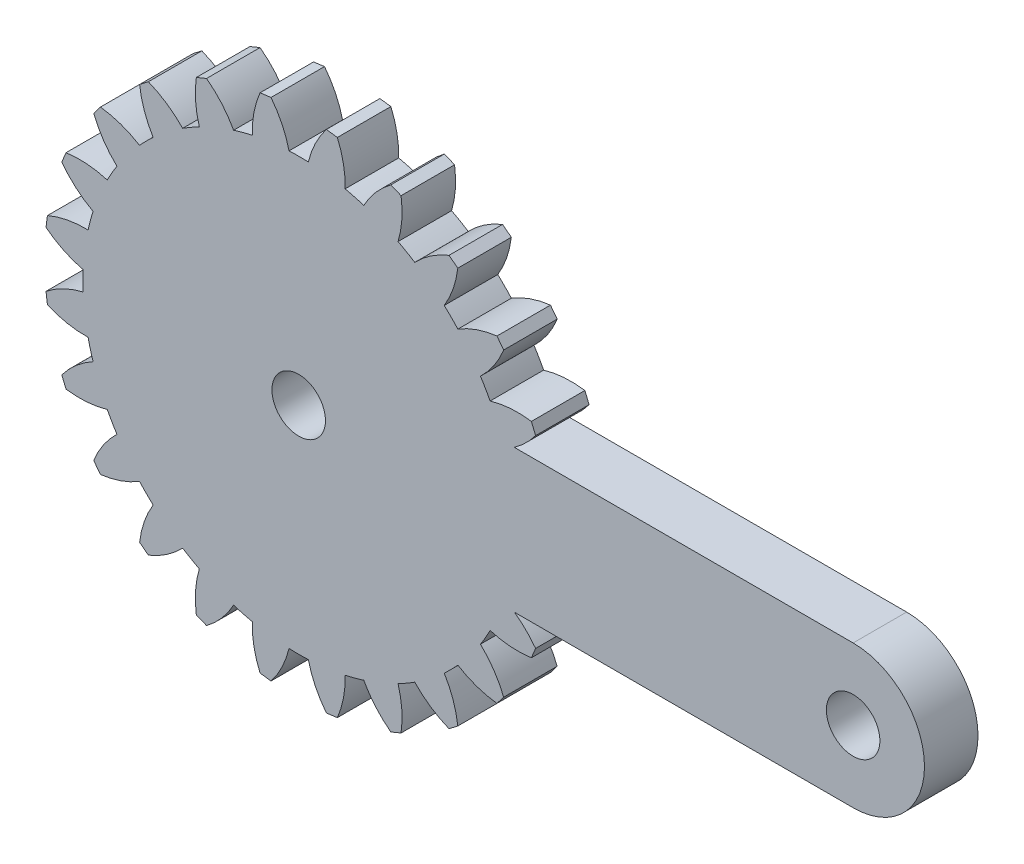
SolidWorks part; units mm, degrees
ref_plane "Front Plane" through (0, 0, 0) normal (0, 0, 1) x (1, 0, 0)
ref_plane "Top Plane" through (0, 0, 0) normal (0, 1, 0) x (1, 0, 0)
ref_plane "Right Plane" through (0, 0, 0) normal (1, 0, 0) x (0, 0, -1)
sketch "Sketch1" plane through (0, 0, 0) normal (0, 0, 1) x (1, 0, 0)
  line L0 (0, 0) -> (18.91, 0) construction
  line L1 (-0.08, 4) -> (18.91, 4)
  line L2 (-0.08, -4) -> (18.91, -4)
  line L3 (-10.0031, 14.0843) -> (-10.6178, 14.1652)
  line L4 (-12.17, 0) -> (-9.0712, 23.5377) construction
  line L5 (-12.17, -30.3062) -> (-12.17, 19.7851) construction
  line L6 (-39.8017, 0) -> (32.0176, 0) construction
  line L7 (-14.3369, 14.0843) -> (-13.7222, 14.1652)
  line L8 (-12.17, 0) -> (-15.0661, 21.9982) construction
  line L9 (-12.17, 0) -> (-9.2739, 21.9982) construction
  line L10 (-12.17, 0) -> (-3.679, 20.499) construction
  line L11 (-12.17, 0) -> (1.3372, 17.6029) construction
  line L12 (-12.17, 0) -> (5.4329, 13.5072) construction
  line L13 (-12.17, 0) -> (8.329, 8.491) construction
  line L14 (-12.17, 0) -> (9.8282, 2.8961) construction
  line L15 (-12.17, 0) -> (9.8282, -2.8961) construction
  line L16 (-12.17, 0) -> (8.329, -8.491) construction
  line L17 (-12.17, 0) -> (5.4329, -13.5072) construction
  line L18 (-12.17, 0) -> (1.3372, -17.6029) construction
  line L19 (-12.17, 0) -> (-3.679, -20.499) construction
  line L20 (-12.17, 0) -> (-9.2739, -21.9982) construction
  line L21 (-12.17, 0) -> (-15.0661, -21.9982) construction
  line L22 (-12.17, 0) -> (-20.661, -20.499) construction
  line L23 (-12.17, 0) -> (-25.6772, -17.6029) construction
  line L24 (-12.17, 0) -> (-29.7729, -13.5072) construction
  line L25 (-12.17, 0) -> (-32.669, -8.491) construction
  line L26 (-12.17, 0) -> (-34.1682, -2.8961) construction
  line L27 (-12.17, 0) -> (-34.1682, 2.8961) construction
  line L28 (-12.17, 0) -> (-32.669, 8.491) construction
  line L29 (-12.17, 0) -> (-29.7729, 13.5072) construction
  line L30 (-12.17, 0) -> (-25.6772, 17.6029) construction
  line L31 (-12.17, 0) -> (-20.661, 20.499) construction
  line L32 (-20.5969, 11.4913) -> (-21.0887, 11.1139)
  line L33 (-26.2543, -2.1669) -> (-26.3352, -1.5522)
  line L34 (-23.6613, 8.4269) -> (-23.2839, 8.9187)
  line L35 (-17.3355, 13.2808) -> (-17.9084, 13.0435)
  line L36 (-25.4508, 5.1655) -> (-25.2135, 5.7384)
  line L37 (-26.2543, 2.1669) -> (-26.3352, 1.5522)
  line L38 (-25.2135, -5.7384) -> (-25.4508, -5.1655)
  line L39 (-21.0887, -11.1139) -> (-20.5969, -11.4913)
  line L40 (-23.6613, -8.4269) -> (-23.2839, -8.9187)
  line L41 (-17.3355, -13.2808) -> (-17.9084, -13.0435)
  line L42 (-13.7222, -14.1652) -> (-14.3369, -14.0843)
  line L43 (-10.6178, -14.1652) -> (-10.0031, -14.0843)
  line L44 (-7.0045, -13.2808) -> (-6.4316, -13.0435)
  line L45 (-3.2513, -11.1139) -> (-3.7431, -11.4913)
  line L46 (-0.6787, -8.4269) -> (-1.0561, -8.9187)
  line L47 (0.8735, -5.7384) -> (1.1108, -5.1655)
  line L48 (-6.4316, 13.0435) -> (-7.0045, 13.2808)
  line L49 (-3.7431, 11.4913) -> (-3.2513, 11.1139)
  line L50 (-1.0561, 8.9187) -> (-0.6787, 8.4269)
  line L51 (1.1108, 5.1655) -> (0.8735, 5.7384)
  arc A0 (-0.08, 4) -> (-0.0808, 4) centre (0, 0) ccw
  arc A1 (18.91, -4) -> (18.91, 4) centre (18.91, 0) ccw
  circle A2 centre (-12.17, 0) radius 1.5
  circle A3 centre (18.91, 0) radius 1.5
  arc A5 (-17.3355, 13.2808) -> (-17.9084, 13.0435) centre (-12.17, 0) ccw
  arc A8 (-9.5667, 11.8064) -> (-10.0031, 14.0843) centre (-14.9647, 11.953) ccw
  arc A9 (-11.6289, 12.0779) -> (-10.6178, 14.1652) centre (-6.3769, 10.8224) cw
  arc A10 (-0.0808, -4) -> (-0.08, -4) centre (0, 0) ccw
  arc A11 (-12.7111, 12.0779) -> (-13.7222, 14.1652) centre (-17.9631, 10.8224) ccw
  arc A12 (-14.7733, 11.8064) -> (-14.3369, 14.0843) centre (-9.3753, 11.953) cw
  arc A13 (-18.6776, 10.1892) -> (-20.5969, 11.4913) centre (-22.5982, 6.4759) ccw
  arc A14 (-20.3277, 8.923) -> (-21.0887, 11.1139) centre (-15.7262, 11.7489) cw
  arc A15 (-24.2479, -0.5411) -> (-26.3352, -1.5522) centre (-22.9924, -5.7931) ccw
  arc A16 (-23.9764, -2.6033) -> (-26.2543, -2.1669) centre (-24.123, 2.7947) cw
  arc A17 (-21.093, 8.1577) -> (-23.2839, 8.9187) centre (-23.9189, 3.5562) ccw
  arc A18 (-22.3592, 6.5076) -> (-23.6613, 8.4269) centre (-18.6459, 10.4282) cw
  arc A19 (-15.8187, 11.5263) -> (-17.3355, 13.2808) centre (-20.5668, 8.9542) ccw
  arc A20 (-17.7403, 10.7303) -> (-17.9084, 13.0435) centre (-12.5642, 12.269) cw
  arc A21 (-22.9003, 5.5703) -> (-25.2135, 5.7384) centre (-24.439, 0.3942) ccw
  arc A22 (-23.6963, 3.6487) -> (-25.4508, 5.1655) centre (-21.1242, 8.3968) cw
  arc A23 (-23.9764, 2.6033) -> (-26.2543, 2.1669) centre (-24.123, -2.7947) ccw
  arc A24 (-24.2479, 0.5411) -> (-26.3352, 1.5522) centre (-22.9924, 5.7931) cw
  arc A25 (-23.6963, -3.6487) -> (-25.4508, -5.1655) centre (-21.1242, -8.3968) ccw
  arc A26 (-22.9003, -5.5703) -> (-25.2135, -5.7384) centre (-24.439, -0.3942) cw
  arc A27 (-20.3277, -8.923) -> (-21.0887, -11.1139) centre (-15.7262, -11.7489) ccw
  arc A28 (-18.6776, -10.1892) -> (-20.5969, -11.4913) centre (-22.5982, -6.4759) cw
  arc A29 (-22.3592, -6.5076) -> (-23.6613, -8.4269) centre (-18.6459, -10.4282) ccw
  arc A30 (-21.093, -8.1577) -> (-23.2839, -8.9187) centre (-23.9189, -3.5562) cw
  arc A31 (-17.7403, -10.7303) -> (-17.9084, -13.0435) centre (-12.5642, -12.269) ccw
  arc A32 (-15.8187, -11.5263) -> (-17.3355, -13.2808) centre (-20.5668, -8.9542) cw
  arc A33 (-14.7733, -11.8064) -> (-14.3369, -14.0843) centre (-9.3753, -11.953) ccw
  arc A34 (-12.7111, -12.0779) -> (-13.7222, -14.1652) centre (-17.9631, -10.8224) cw
  arc A35 (-11.6289, -12.0779) -> (-10.6178, -14.1652) centre (-6.3769, -10.8224) ccw
  arc A36 (-9.5667, -11.8064) -> (-10.0031, -14.0843) centre (-14.9647, -11.953) cw
  arc A37 (-8.5213, -11.5263) -> (-7.0045, -13.2808) centre (-3.7732, -8.9542) ccw
  arc A38 (-6.5997, -10.7303) -> (-6.4316, -13.0435) centre (-11.7758, -12.269) cw
  arc A39 (-5.6624, -10.1892) -> (-3.7431, -11.4913) centre (-1.7418, -6.4759) ccw
  arc A40 (-4.0123, -8.923) -> (-3.2513, -11.1139) centre (-8.6138, -11.7489) cw
  arc A41 (-3.247, -8.1577) -> (-1.0561, -8.9187) centre (-0.4211, -3.5562) ccw
  arc A42 (-1.9808, -6.5076) -> (-0.6787, -8.4269) centre (-5.6941, -10.4282) cw
  arc A43 (-1.4397, -5.5703) -> (0.8735, -5.7384) centre (0.099, -0.3942) ccw
  arc A44 (-0.0808, -4) -> (1.1108, -5.1655) centre (-3.2158, -8.3968) cw
  arc A45 (-8.5213, 11.5263) -> (-7.0045, 13.2808) centre (-3.7732, 8.9542) cw
  arc A46 (-6.5997, 10.7303) -> (-6.4316, 13.0435) centre (-11.7758, 12.269) ccw
  arc A47 (-5.6624, 10.1892) -> (-3.7431, 11.4913) centre (-1.7418, 6.4759) cw
  arc A48 (-4.0123, 8.923) -> (-3.2513, 11.1139) centre (-8.6138, 11.7489) ccw
  arc A49 (-3.247, 8.1577) -> (-1.0561, 8.9187) centre (-0.4211, 3.5562) cw
  arc A50 (-1.9808, 6.5076) -> (-0.6787, 8.4269) centre (-5.6941, 10.4282) ccw
  arc A51 (-1.4397, 5.5703) -> (0.8735, 5.7384) centre (0.099, 0.3942) cw
  arc A52 (-0.0808, 4) -> (1.1108, 5.1655) centre (-3.2158, 8.3968) ccw
  arc A53 (-1.4397, 5.5703) -> (-1.9808, 6.5076) centre (-12.17, 0) ccw
  arc A54 (-3.247, 8.1577) -> (-4.0123, 8.923) centre (-12.17, 0) ccw
  arc A55 (-5.6624, 10.1892) -> (-6.5997, 10.7303) centre (-12.17, 0) ccw
  arc A56 (-8.5213, 11.5263) -> (-9.5667, 11.8064) centre (-12.17, 0) ccw
  arc A57 (-11.6289, 12.0779) -> (-12.7111, 12.0779) centre (-12.17, 0) ccw
  arc A58 (-14.7733, 11.8064) -> (-15.8187, 11.5263) centre (-12.17, 0) ccw
  arc A59 (-17.7403, 10.7303) -> (-18.6776, 10.1892) centre (-12.17, 0) ccw
  arc A60 (-20.3277, 8.923) -> (-21.093, 8.1577) centre (-12.17, 0) ccw
  arc A61 (-22.3592, 6.5076) -> (-22.9003, 5.5703) centre (-12.17, 0) ccw
  arc A62 (-23.6963, 3.6487) -> (-23.9764, 2.6033) centre (-12.17, 0) ccw
  arc A63 (-24.2479, 0.5411) -> (-24.2479, -0.5411) centre (-12.17, 0) ccw
  arc A64 (-23.9764, -2.6033) -> (-23.6963, -3.6487) centre (-12.17, 0) ccw
  arc A65 (-22.9003, -5.5703) -> (-22.3592, -6.5076) centre (-12.17, 0) ccw
  arc A66 (-21.093, -8.1577) -> (-20.3277, -8.923) centre (-12.17, 0) ccw
  arc A67 (-15.8187, -11.5263) -> (-14.7733, -11.8064) centre (-12.17, 0) ccw
  arc A68 (-18.6776, -10.1892) -> (-17.7403, -10.7303) centre (-12.17, 0) ccw
  arc A69 (-12.7111, -12.0779) -> (-11.6289, -12.0779) centre (-12.17, 0) ccw
  arc A70 (-9.5667, -11.8064) -> (-8.5213, -11.5263) centre (-12.17, 0) ccw
  arc A71 (-6.5997, -10.7303) -> (-5.6624, -10.1892) centre (-12.17, 0) ccw
  arc A72 (-4.0123, -8.923) -> (-3.247, -8.1577) centre (-12.17, 0) ccw
  arc A73 (-1.9808, -6.5076) -> (-1.4397, -5.5703) centre (-12.17, 0) ccw
  arc A74 (-13.7222, 14.1652) -> (-14.3369, 14.0843) centre (-12.17, 0) ccw
  arc A75 (-10.0031, 14.0843) -> (-10.6178, 14.1652) centre (-12.17, 0) ccw
  arc A76 (-6.4316, 13.0435) -> (-7.0045, 13.2808) centre (-12.17, 0) ccw
  arc A77 (-3.2513, 11.1139) -> (-3.7431, 11.4913) centre (-12.17, 0) ccw
  arc A78 (-0.6787, 8.4269) -> (-1.0561, 8.9187) centre (-12.17, 0) ccw
  arc A79 (-20.5969, 11.4913) -> (-21.0887, 11.1139) centre (-12.17, 0) ccw
  arc A80 (-25.2135, 5.7384) -> (-25.4508, 5.1655) centre (-12.17, 0) ccw
  arc A81 (-23.2839, 8.9187) -> (-23.6613, 8.4269) centre (-12.17, 0) ccw
  arc A82 (-26.2543, 2.1669) -> (-26.3352, 1.5522) centre (-12.17, 0) ccw
  arc A83 (-26.3352, -1.5522) -> (-26.2543, -2.1669) centre (-12.17, 0) ccw
  arc A84 (-25.4508, -5.1655) -> (-25.2135, -5.7384) centre (-12.17, 0) ccw
  arc A85 (-23.6613, -8.4269) -> (-23.2839, -8.9187) centre (-12.17, 0) ccw
  arc A86 (-21.0887, -11.1139) -> (-20.5969, -11.4913) centre (-12.17, 0) ccw
  arc A87 (-17.9084, -13.0435) -> (-17.3355, -13.2808) centre (-12.17, 0) ccw
  arc A88 (-10.6178, -14.1652) -> (-10.0031, -14.0843) centre (-12.17, 0) ccw
  arc A89 (-14.3369, -14.0843) -> (-13.7222, -14.1652) centre (-12.17, 0) ccw
  arc A90 (-7.0045, -13.2808) -> (-6.4316, -13.0435) centre (-12.17, 0) ccw
  arc A91 (-3.7431, -11.4913) -> (-3.2513, -11.1139) centre (-12.17, 0) ccw
  arc A92 (-1.0561, -8.9187) -> (-0.6787, -8.4269) centre (-12.17, 0) ccw
  arc A93 (0.8735, -5.7384) -> (1.1108, -5.1655) centre (-12.17, 0) ccw
  arc A94 (1.1108, 5.1655) -> (0.8735, 5.7384) centre (-12.17, 0) ccw
  point P3 (9.495, 0)
  dimension "D2" = 4
  dimension "D4" = 3
  dimension "D5" = 3
  dimension "D6" = 28.5
  dimension "D8" = 10.8
  dimension "D1" = 18.91
  dimension "D3" = 31.08
  dimension "D7" = 7.5
  dimension "D9" = 1.04
  dimension "D10" = 0.31
  dimension "D11" = 18.99
  dimension "D12" = 8
  dimension "D14" = 0.31
  dimension "D15" = 24
extrude "Boss-Extrude1" add sketch "Sketch1" along normal blind 3 contours A42 A73 A43 L47 A44 A10 L2 A1 L1 A0 A52 L51 A51 A53 A50 L50 A49 A54 A48 L49 A47 A55 A46 L48 A45 A56 A8 L3 A9 A57 A11 L7 A12 A58 A19 L35 A20 A59 A13 L32 A14 A60 A17 L34 A18 A61 A21 L36 A22 A62 A23
